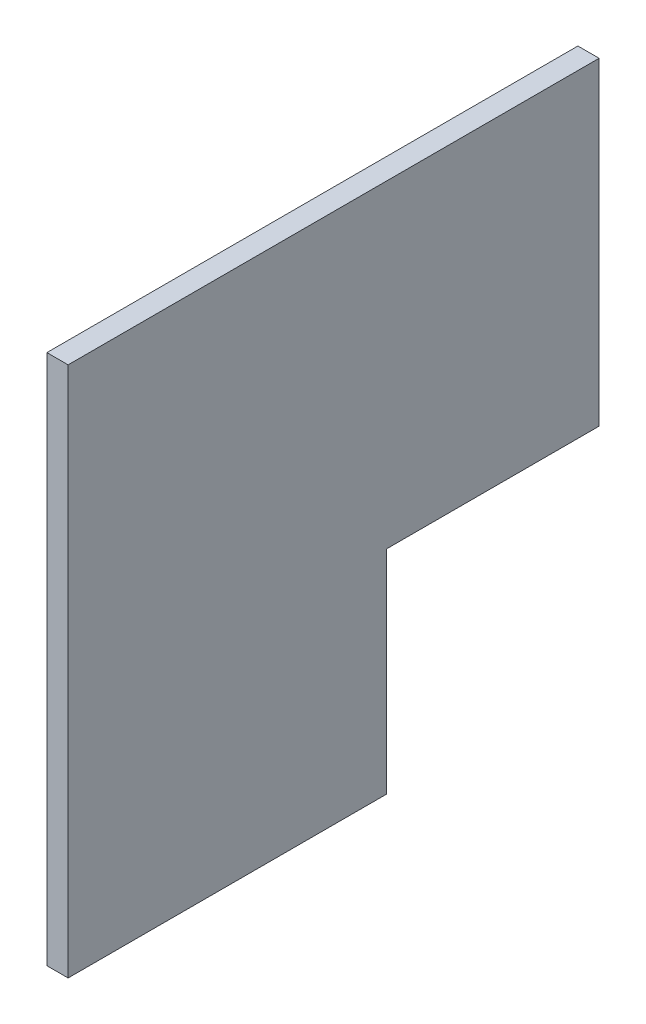
SolidWorks part; units mm, degrees
other "Thermal 1"
material "Concrete"
ref_plane "Front Plane" through (0, 0, 0) normal (1, 0, 0) x (0, 1, 0)
ref_plane "Top Plane" through (0, 0, 0) normal (0, 0, 1) x (0, 1, 0)
ref_plane "Right Plane" through (0, 0, 0) normal (0, 1, 0) x (-1, 0, 0)
sketch "Sketch1" plane through (0, 0, 0) normal (1, 0, 0) x (0, 1, 0)
  line L0 (0, 100) -> (100, 100)
  line L5 (100, 100) -> (100, 0)
  line L6 (100, 0) -> (250, 0)
  line L7 (250, 0) -> (250, 250)
  line L8 (250, 250) -> (0, 250)
  line L9 (0, 250) -> (0, 100)
  point P3 (0, 0)
  dimension "D1" = 100
  dimension "D2" = 250
extrude "Boss-Extrude1" add sketch "Sketch1" along normal blind 10 contours L6 L7 L8 L9 L0 L5
